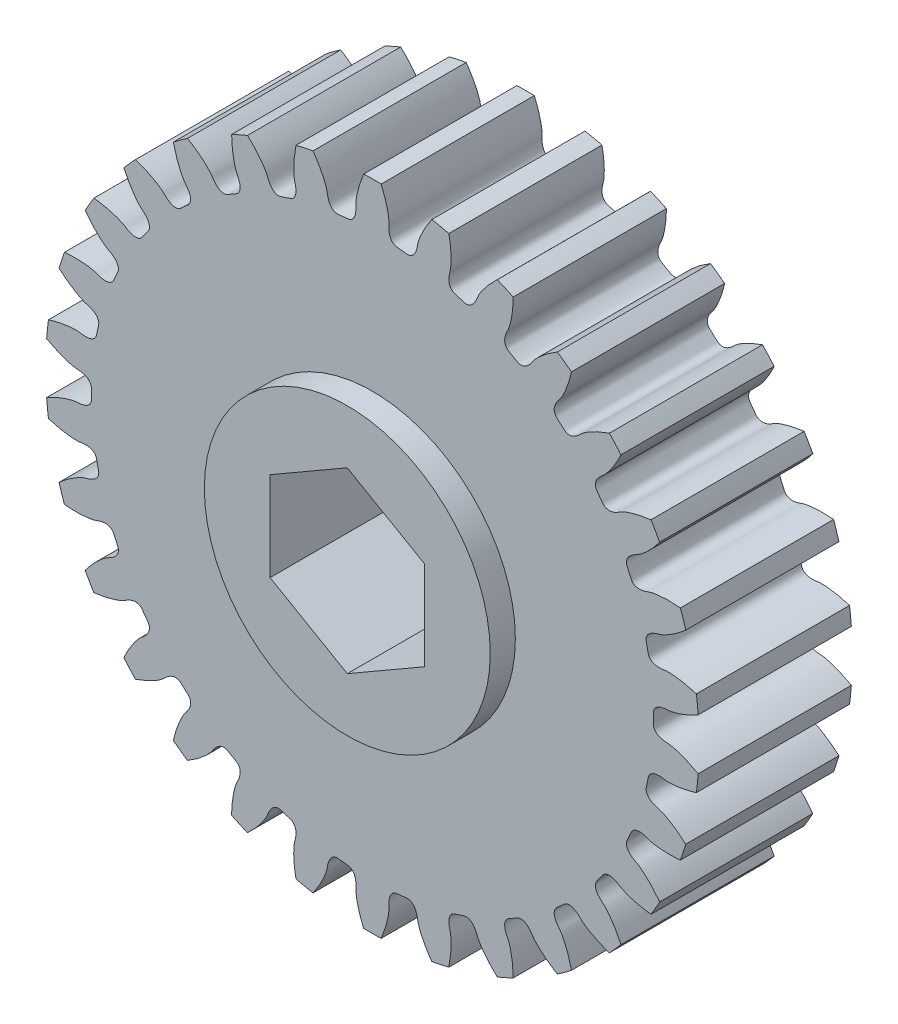
SolidWorks part; units mm, degrees
ref_plane "Front Plane" through (0, 0, 0) normal (0, 0, 1) x (1, 0, 0)
ref_plane "Top Plane" through (0, 0, 0) normal (0, 1, 0) x (1, 0, 0)
ref_plane "Right Plane" through (0, 0, 0) normal (1, 0, 0) x (0, 0, -1)
ref_plane "Plane1" through (0, 0, 4.7625) normal (0, 0, 1) x (1, 0, 0)
sketch "Sketch1" plane through (0, 0, 4.7625) normal (0, 0, 1) x (1, 0, 0)
  arc A0 (20.258, 1.5856) -> (20.145, 2.661) centre (0, 0) ccw
  arc A1 (19.4857, 5.7628) -> (19.1516, 6.7912) centre (0, 0) ccw
  arc A2 (17.8617, 9.6882) -> (17.3211, 10.6246) centre (0, 0) ccw
  arc A3 (15.4571, 13.1901) -> (14.7336, 13.9937) centre (0, 0) ccw
  arc A4 (12.377, 16.1156) -> (11.5022, 16.7512) centre (0, 0) ccw
  arc A5 (8.7559, 18.3368) -> (7.768, 18.7766) centre (0, 0) ccw
  arc A6 (4.7521, 19.7565) -> (3.6944, 19.9813) centre (0, 0) ccw
  arc A7 (0.5407, 20.3128) -> (-0.5407, 20.3128) centre (0, 0) ccw
  arc A8 (-3.6944, 19.9813) -> (-4.7521, 19.7565) centre (0, 0) ccw
  arc A9 (-7.768, 18.7766) -> (-8.7559, 18.3368) centre (0, 0) ccw
  arc A10 (-11.5022, 16.7512) -> (-12.377, 16.1156) centre (0, 0) ccw
  arc A11 (-14.7336, 13.9937) -> (-15.4571, 13.1901) centre (0, 0) ccw
  arc A12 (-17.3211, 10.6246) -> (-17.8617, 9.6882) centre (0, 0) ccw
  arc A13 (-19.1516, 6.7912) -> (-19.4857, 5.7628) centre (0, 0) ccw
  arc A14 (-20.145, 2.661) -> (-20.258, 1.5856) centre (0, 0) ccw
  arc A15 (-20.258, -1.5856) -> (-20.145, -2.661) centre (0, 0) ccw
  arc A16 (-19.4857, -5.7628) -> (-19.1516, -6.7912) centre (0, 0) ccw
  arc A17 (-17.8617, -9.6882) -> (-17.3211, -10.6246) centre (0, 0) ccw
  arc A18 (-15.4571, -13.1901) -> (-14.7336, -13.9937) centre (0, 0) ccw
  arc A19 (-12.377, -16.1156) -> (-11.5022, -16.7512) centre (0, 0) ccw
  arc A20 (-8.7559, -18.3368) -> (-7.768, -18.7766) centre (0, 0) ccw
  arc A21 (-4.7521, -19.7565) -> (-3.6944, -19.9813) centre (0, 0) ccw
  arc A22 (-0.5407, -20.3128) -> (0.5407, -20.3128) centre (0, 0) ccw
  arc A23 (3.6944, -19.9813) -> (4.7521, -19.7565) centre (0, 0) ccw
  arc A24 (7.768, -18.7766) -> (8.7559, -18.3368) centre (0, 0) ccw
  arc A25 (11.5022, -16.7512) -> (12.377, -16.1156) centre (0, 0) ccw
  arc A26 (14.7336, -13.9937) -> (15.4571, -13.1901) centre (0, 0) ccw
  arc A27 (17.3211, -10.6246) -> (17.8617, -9.6882) centre (0, 0) ccw
  arc A28 (19.1516, -6.7912) -> (19.4857, -5.7628) centre (0, 0) ccw
  arc A29 (20.145, -2.661) -> (20.258, -1.5856) centre (0, 0) ccw
  spline S0 degree 3 number of poles 93 (20.258, 1.5856) -> (20.258, -1.5856)
  spline S1 degree 3 number of poles 93 (19.4857, 5.7628) -> (20.145, 2.661)
  spline S2 degree 3 number of poles 93 (17.8617, 9.6882) -> (19.1516, 6.7912)
  spline S3 degree 3 number of poles 93 (15.4571, 13.1901) -> (17.3211, 10.6246)
  spline S4 degree 3 number of poles 93 (12.377, 16.1156) -> (14.7336, 13.9937)
  spline S5 degree 3 number of poles 93 (8.7559, 18.3368) -> (11.5022, 16.7512)
  spline S6 degree 3 number of poles 93 (4.7521, 19.7565) -> (7.768, 18.7766)
  spline S7 degree 3 number of poles 93 (0.5407, 20.3128) -> (3.6944, 19.9813)
  spline S8 degree 3 number of poles 93 (-3.6944, 19.9813) -> (-0.5407, 20.3128)
  spline S9 degree 3 number of poles 93 (-7.768, 18.7766) -> (-4.7521, 19.7565)
  spline S10 degree 3 number of poles 93 (-11.5022, 16.7512) -> (-8.7559, 18.3368)
  spline S11 degree 3 number of poles 93 (-14.7336, 13.9937) -> (-12.377, 16.1156)
  spline S12 degree 3 number of poles 93 (-17.3211, 10.6246) -> (-15.4571, 13.1901)
  spline S13 degree 3 number of poles 93 (-19.1516, 6.7912) -> (-17.8617, 9.6882)
  spline S14 degree 3 number of poles 93 (-20.145, 2.661) -> (-19.4857, 5.7628)
  spline S15 degree 3 number of poles 93 (-20.258, -1.5856) -> (-20.258, 1.5856)
  spline S16 degree 3 number of poles 93 (-19.4857, -5.7628) -> (-20.145, -2.661)
  spline S17 degree 3 number of poles 93 (-17.8617, -9.6882) -> (-19.1516, -6.7912)
  spline S18 degree 3 number of poles 93 (-15.4571, -13.1901) -> (-17.3211, -10.6246)
  spline S19 degree 3 number of poles 93 (-12.377, -16.1156) -> (-14.7336, -13.9937)
  spline S20 degree 3 number of poles 93 (-8.7559, -18.3368) -> (-11.5022, -16.7512)
  spline S21 degree 3 number of poles 93 (-4.7521, -19.7565) -> (-7.768, -18.7766)
  spline S22 degree 3 number of poles 93 (-0.5407, -20.3128) -> (-3.6944, -19.9813)
  spline S23 degree 3 number of poles 93 (3.6944, -19.9813) -> (0.5407, -20.3128)
  spline S24 degree 3 number of poles 93 (7.768, -18.7766) -> (4.7521, -19.7565)
  spline S25 degree 3 number of poles 93 (11.5022, -16.7512) -> (8.7559, -18.3368)
  spline S26 degree 3 number of poles 93 (14.7336, -13.9937) -> (12.377, -16.1156)
  spline S27 degree 3 number of poles 93 (17.3211, -10.6246) -> (15.4571, -13.1901)
  spline S28 degree 3 number of poles 93 (19.1516, -6.7912) -> (17.8617, -9.6882)
  spline S29 degree 3 number of poles 93 (20.145, -2.661) -> (19.4857, -5.7628)
extrude "Boss-Extrude1" add sketch "Sketch1" against normal blind 9.525
sketch "Sketch2" plane through (0, 0, 4.7625) normal (0, 0, 1) x (1, 0, 0)
  circle A0 centre (0, 0) radius 8.89
extrude "Boss-Extrude2" add sketch "Sketch2" along normal blind 1.5621
sketch "Sketch3" plane through (0, 0, -4.7625) normal (0, 0, -1) x (-1, 0, 0)
  circle A0 centre (0, 0) radius 8.89
extrude "Boss-Extrude3" add sketch "Sketch3" along normal blind 1.5621
sketch "Sketch4" plane through (0, 0, -6.3246) normal (0, 0, -1) x (-1, 0, 0)
  line L0 (4.8006, 2.7716) -> (0, 5.5433)
  line L1 (0, 5.5433) -> (-4.8006, 2.7716)
  line L2 (-4.8006, 2.7716) -> (-4.8006, -2.7716)
  line L3 (-4.8006, -2.7716) -> (0, -5.5433)
  line L4 (0, -5.5433) -> (4.8006, -2.7716)
  line L5 (4.8006, -2.7716) -> (4.8006, 2.7716)
extrude "Cut-Extrude1" cut sketch "Sketch4" against normal through all
